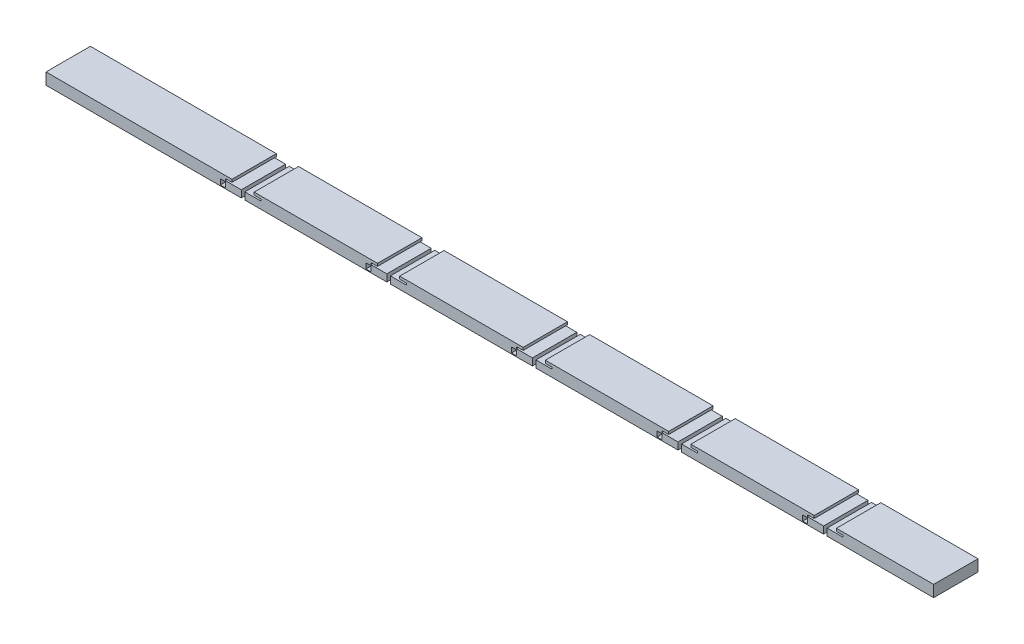
SolidWorks part; units mm, degrees
ref_plane "Front Plane" through (0, 0, 0) normal (0, 0, 1) x (1, 0, 0)
ref_plane "Top Plane" through (0, 0, 0) normal (0, 1, 0) x (1, 0, 0)
ref_plane "Right Plane" through (0, 0, 0) normal (1, 0, 0) x (0, 0, -1)
sketch "Sketch1" plane through (0, 0, 0) normal (0, 1, 0) x (1, 0, 0)
  line L1 (-21.3043, -8.2174) -> (178.6957, -8.2174)
  line L2 (-21.3043, -8.2174) -> (-21.3043, 1.7826)
  line L3 (-21.3043, 1.7826) -> (178.6957, 1.7826)
  line L4 (178.6957, -8.2174) -> (178.6957, 1.7826)
  dimension "D1" = 10
  dimension "D2" = 200
extrude "Boss-Extrude1" add sketch "Sketch1" along normal blind 2.6 contours L1 L4 L3 L2
sketch "Sketch3" plane through (0, 0, 0) normal (0, -1, 0) x (1, 0, 0)
  line L5 (-21.3043, 8.2174) -> (178.6957, 8.2174) construction
  line L6 (22.6957, 8.2174) -> (23.4957, 8.2174)
  line L7 (22.6957, 8.2174) -> (22.6957, -1.7826)
  line L8 (22.6957, -1.7826) -> (23.4957, -1.7826)
  line L9 (23.4957, 8.2174) -> (23.4957, -1.7826)
  line L10 (-21.3043, -1.7826) -> (178.6957, -1.7826) construction
  line L11 (-21.3043, 8.2174) -> (-21.3043, -1.7826) construction
  line L13 (55.4957, 8.2174) -> (56.2957, 8.2174)
  line L14 (55.4957, 8.2174) -> (55.4957, -1.7826)
  line L15 (55.4957, -1.7826) -> (56.2957, -1.7826)
  line L16 (56.2957, 8.2174) -> (56.2957, -1.7826)
  line L17 (88.2957, 8.2174) -> (89.0957, 8.2174)
  line L18 (88.2957, 8.2174) -> (88.2957, -1.7826)
  line L19 (88.2957, -1.7826) -> (89.0957, -1.7826)
  line L20 (89.0957, 8.2174) -> (89.0957, -1.7826)
  line L21 (121.0957, 8.2174) -> (121.8957, 8.2174)
  line L22 (121.0957, 8.2174) -> (121.0957, -1.7826)
  line L23 (121.0957, -1.7826) -> (121.8957, -1.7826)
  line L24 (121.8957, 8.2174) -> (121.8957, -1.7826)
  line L25 (153.8957, 8.2174) -> (154.6957, 8.2174)
  line L26 (153.8957, 8.2174) -> (153.8957, -1.7826)
  line L27 (153.8957, -1.7826) -> (154.6957, -1.7826)
  line L28 (154.6957, 8.2174) -> (154.6957, -1.7826)
  dimension "D1" = 0.8
  dimension "D2" = 44
  dimension "D3" = 0.8
  dimension "D4" = 32
  dimension "D5" = 0.8
  dimension "D6" = 32
  dimension "D7" = 0.8
  dimension "D8" = 0.8
  dimension "D9" = 32
  dimension "D10" = 32
extrude "Cut-Extrude1" cut sketch "Sketch3" against normal blind 2
sketch "Sketch4" plane through (0, 2.6, 0) normal (0, 1, 0) x (1, 0, 0)
  line L0 (-21.3043, 1.7826) -> (178.6957, 1.7826) construction
  line L1 (151.7957, 1.7826) -> (156.7957, 1.7826)
  line L2 (151.7957, 1.7826) -> (151.7957, -8.2174)
  line L3 (151.7957, -8.2174) -> (156.7957, -8.2174)
  line L4 (156.7957, 1.7826) -> (156.7957, -8.2174)
  line L5 (-21.3043, -8.2174) -> (178.6957, -8.2174) construction
  line L7 (123.9957, 1.7826) -> (118.9957, 1.7826)
  line L8 (123.9957, 1.7826) -> (123.9957, -8.2174)
  line L9 (123.9957, -8.2174) -> (118.9957, -8.2174)
  line L10 (118.9957, 1.7826) -> (118.9957, -8.2174)
  line L11 (91.1957, 1.7826) -> (86.1957, 1.7826)
  line L12 (91.1957, 1.7826) -> (91.1957, -8.2174)
  line L13 (91.1957, -8.2174) -> (86.1957, -8.2174)
  line L14 (86.1957, 1.7826) -> (86.1957, -8.2174)
  line L16 (53.3957, 1.7826) -> (58.3957, 1.7826)
  line L17 (53.3957, 1.7826) -> (53.3957, -8.2174)
  line L18 (53.3957, -8.2174) -> (58.3957, -8.2174)
  line L19 (58.3957, 1.7826) -> (58.3957, -8.2174)
  line L20 (20.5957, 1.7826) -> (25.5957, 1.7826)
  line L21 (20.5957, 1.7826) -> (20.5957, -8.2174)
  line L22 (20.5957, -8.2174) -> (25.5957, -8.2174)
  line L23 (25.5957, 1.7826) -> (25.5957, -8.2174)
  line L26 (-21.3043, -8.2174) -> (-21.3043, 1.7826) construction
  dimension "D1" = 5
  dimension "D2" = 27.8
  dimension "D3" = 41.9
  dimension "D4" = 5
  dimension "D5" = 5
  dimension "D6" = 27.8
  dimension "D7" = 5
  dimension "D8" = 5
  dimension "D9" = 27.8
  dimension "D10" = 27.8
extrude "Cut-Extrude2" cut sketch "Sketch4" against normal blind 0.6
sketch "Sketch5" plane through (0, 2, 0) normal (0, 1, 0) x (1, 0, 0)
  line L0 (118.9957, -8.2174) -> (121.0957, -8.2174) construction
  line L1 (86.1957, 1.7826) -> (91.1957, 1.7826)
  line L2 (86.1957, 1.7826) -> (86.1957, -8.2174)
  line L3 (86.1957, -8.2174) -> (91.1957, -8.2174)
  line L4 (91.1957, 1.7826) -> (91.1957, -8.2174)
  line L5 (118.9957, 1.7826) -> (123.9957, 1.7826)
  line L6 (118.9957, 1.7826) -> (118.9957, -8.2174)
  line L7 (118.9957, -8.2174) -> (123.9957, -8.2174)
  line L8 (123.9957, 1.7826) -> (123.9957, -8.2174)
  line L9 (123.9957, -8.2174) -> (123.9957, 1.7826) construction
  line L11 (151.7957, 1.7826) -> (156.7957, 1.7826)
  line L12 (151.7957, 1.7826) -> (151.7957, -8.2174)
  line L13 (151.7957, -8.2174) -> (156.7957, -8.2174)
  line L14 (156.7957, 1.7826) -> (156.7957, -8.2174)
  line L15 (53.3957, 1.7826) -> (58.3957, 1.7826)
  line L16 (53.3957, 1.7826) -> (53.3957, -8.2174)
  line L17 (53.3957, -8.2174) -> (58.3957, -8.2174)
  line L18 (58.3957, 1.7826) -> (58.3957, -8.2174)
  line L19 (20.5957, 1.7826) -> (25.5957, 1.7826)
  line L20 (20.5957, 1.7826) -> (20.5957, -8.2174)
  line L21 (20.5957, -8.2174) -> (25.5957, -8.2174)
  line L22 (25.5957, 1.7826) -> (25.5957, -8.2174)
extrude "Boss-Extrude2" add sketch "Sketch5" along normal blind 0.6 separate body
ref_plane "Plane1" through (0, 2, 0) normal (0, 1, 0) x (1, 0, 0)
sketch "Sketch6" plane through (0, 2, 0) normal (0, 1, 0) x (1, 0, 0)
  line L0 (156.7957, 1.7826) -> (151.7957, 1.7826) construction
  line L2 (154.6957, 1.7826) -> (154.6957, -8.2174)
  line L5 (25.5957, -8.2174) -> (53.3957, -8.2174) construction
  line L6 (23.4957, 1.7826) -> (27.0957, 1.7826)
  line L8 (153.8957, 1.7826) -> (153.8957, -8.2174)
  line L11 (156.7957, -8.2174) -> (156.7957, 1.7826) construction
  line L13 (121.8957, 1.7826) -> (121.8957, -8.2174)
  line L17 (121.0957, 1.7826) -> (121.0957, -8.2174)
  line L20 (118.9957, 1.7826) -> (118.9957, -8.2174) construction
  line L25 (89.0957, 1.7826) -> (89.0957, -8.2174)
  line L29 (88.2957, 1.7826) -> (88.2957, -8.2174)
  line L33 (56.2957, 1.7826) -> (56.2957, -8.2174)
  line L37 (55.4957, 1.7826) -> (55.4957, -8.2174)
  line L48 (53.3957, 1.7826) -> (53.3957, -8.2174) construction
  line L50 (23.4957, 1.7826) -> (23.4957, -8.2174)
  line L51 (23.4957, -8.2174) -> (27.0957, -8.2174)
  line L54 (86.1957, 1.7826) -> (86.1957, -8.2174) construction
  line L121 (27.0957, 1.7826) -> (27.0957, -8.2174)
  line L122 (25.5957, 1.7826) -> (20.5957, 1.7826) construction
  line L123 (22.6957, 1.7826) -> (19.0957, 1.7826)
  line L124 (22.6957, 1.7826) -> (22.6957, -8.2174)
  line L125 (22.6957, -8.2174) -> (19.0957, -8.2174)
  line L126 (19.0957, 1.7826) -> (19.0957, -8.2174)
  line L127 (-21.3043, -8.2174) -> (20.5957, -8.2174) construction
  line L128 (20.5957, 1.7826) -> (20.5957, -8.2174) construction
  line L130 (58.3957, 1.7826) -> (86.1957, 1.7826) construction
  line L140 (56.2957, 1.7826) -> (59.8957, 1.7826)
  line L141 (59.8957, 1.7826) -> (59.8957, -8.2174)
  line L142 (58.3957, -8.2174) -> (86.1957, -8.2174) construction
  line L143 (59.8957, -8.2174) -> (56.2957, -8.2174)
  line L144 (55.4957, 1.7826) -> (51.8957, 1.7826)
  line L145 (25.5957, 1.7826) -> (53.3957, 1.7826) construction
  line L146 (51.8957, 1.7826) -> (51.8957, -8.2174)
  line L147 (51.8957, -8.2174) -> (55.4957, -8.2174)
  line L148 (88.2957, 1.7826) -> (84.6957, 1.7826)
  line L149 (89.0957, 1.7826) -> (92.6957, 1.7826)
  line L150 (91.1957, 1.7826) -> (118.9957, 1.7826) construction
  line L151 (84.6957, 1.7826) -> (84.6957, -8.2174)
  line L152 (84.6957, -8.2174) -> (88.2957, -8.2174)
  line L153 (92.6957, 1.7826) -> (92.6957, -8.2174)
  line L154 (91.1957, -8.2174) -> (118.9957, -8.2174) construction
  line L155 (92.6957, -8.2174) -> (89.0957, -8.2174)
  line L156 (121.0957, -8.2174) -> (117.4957, -8.2174)
  line L157 (121.8957, -8.2174) -> (125.4957, -8.2174)
  line L158 (123.9957, -8.2174) -> (151.7957, -8.2174) construction
  line L159 (117.4957, -8.2174) -> (117.4957, 1.7826)
  line L160 (117.4957, 1.7826) -> (121.0957, 1.7826)
  line L161 (125.4957, -8.2174) -> (125.4957, 1.7826)
  line L162 (123.9957, 1.7826) -> (151.7957, 1.7826) construction
  line L163 (125.4957, 1.7826) -> (121.8957, 1.7826)
  line L164 (154.6957, -8.2174) -> (158.2957, -8.2174)
  line L165 (156.7957, -8.2174) -> (178.6957, -8.2174) construction
  line L166 (153.8957, -8.2174) -> (150.2957, -8.2174)
  line L167 (150.2957, -8.2174) -> (150.2957, 1.7826)
  line L168 (150.2957, 1.7826) -> (153.8957, 1.7826)
  line L169 (158.2957, -8.2174) -> (158.2957, 1.7826)
  line L170 (156.7957, 1.7826) -> (178.6957, 1.7826) construction
  line L171 (158.2957, 1.7826) -> (154.6957, 1.7826)
  dimension "D1" = 0.8
  dimension "D2" = 2.1
  dimension "D3" = 3.6
  dimension "D5" = 0.8
  dimension "D6" = 3.6
  dimension "D8" = 2.1
  dimension "D9" = 0.8
  dimension "D12" = 0.8
  dimension "D13" = 3.6
  dimension "D15" = 3.6
  dimension "D16" = 0.8
  dimension "D17" = 3.6
  dimension "D18" = 2.1
  dimension "D19" = 2.1
  dimension "D21" = 2.1
extrude "Cut-Extrude3" cut sketch "Sketch6" against normal blind 0.4
sketch "Sketch11" plane through (0, 0, 8.2174) normal (0, 0, 1) x (1, 0, 0)
  line L0 (86.1957, 2.6) -> (86.1957, 2) construction
  line L5 (118.9957, 2) -> (118.9957, 2.6) construction
  line L6 (151.7957, 2.6) -> (151.7957, 2) construction
  line L39 (53.3957, 2.6) -> (53.3957, 2) construction
  line L44 (20.5957, 2.6) -> (20.5957, 2) construction
  line L49 (19.0957, 1.4) -> (17.9957, 1.4)
  line L54 (19.0957, 1.4) -> (19.0957, 0.2)
  line L79 (19.0957, 0.2) -> (17.9957, 0.2)
  line L84 (17.9957, 1.4) -> (17.9957, 0.2)
  line L85 (-21.3043, 2.6) -> (20.5957, 2.6) construction
  line L94 (25.5957, 2.6) -> (53.3957, 2.6) construction
  line L95 (58.3957, 2.6) -> (86.1957, 2.6) construction
  line L96 (91.1957, 2.6) -> (118.9957, 2.6) construction
  line L97 (123.9957, 2.6) -> (151.7957, 2.6) construction
  line L98 (50.7957, 1.4) -> (51.8957, 1.4)
  line L99 (50.7957, 1.4) -> (50.7957, 0.2)
  line L100 (50.7957, 0.2) -> (51.8957, 0.2)
  line L101 (51.8957, 1.4) -> (51.8957, 0.2)
  line L102 (83.5957, 1.4) -> (84.6957, 1.4)
  line L103 (83.5957, 1.4) -> (83.5957, 0.2)
  line L104 (83.5957, 0.2) -> (84.6957, 0.2)
  line L105 (84.6957, 1.4) -> (84.6957, 0.2)
  line L106 (116.3957, 1.4) -> (117.4957, 1.4)
  line L107 (116.3957, 1.4) -> (116.3957, 0.2)
  line L108 (116.3957, 0.2) -> (117.4957, 0.2)
  line L109 (117.4957, 1.4) -> (117.4957, 0.2)
  line L110 (149.1957, 1.4) -> (150.2957, 1.4)
  line L111 (149.1957, 1.4) -> (149.1957, 0.2)
  line L112 (149.1957, 0.2) -> (150.2957, 0.2)
  line L113 (150.2957, 1.4) -> (150.2957, 0.2)
  point P28 (117.4957, 0.8)
  point P33 (151.7957, 2.3)
  dimension "D2" = 1.1
  dimension "D3" = 1.5
  dimension "D4" = 1.1
  dimension "D5" = 1.5
  dimension "D6" = 1.1
  dimension "D7" = 1.5
  dimension "D8" = 1.1
  dimension "D9" = 1.1
  dimension "D10" = 1.5
  dimension "D11" = 1.5
  dimension "D12" = 1.2
  dimension "D13" = 1.2
  dimension "D14" = 1.2
  dimension "D15" = 1.2
  dimension "D16" = 1.2
  dimension "D17" = 1.2
  dimension "D18" = 1.2
  dimension "D19" = 1.2
  dimension "D20" = 1.2
  dimension "D21" = 1.2
extrude "Cut-Extrude4" cut sketch "Sketch11" against normal blind 5
sketch "Sketch12" plane through (0, 2.6, 0) normal (0, 1, 0) x (1, 0, 0)
  line L0 (25.5957, -8.2174) -> (25.5957, 1.7826) construction
  line L1 (20.5957, 1.7826) -> (25.5957, 1.7826)
  line L2 (20.5957, 1.7826) -> (20.5957, -8.2174)
  line L3 (20.5957, -8.2174) -> (25.5957, -8.2174)
  line L4 (25.5957, 1.7826) -> (25.5957, -8.2174)
  line L6 (53.3957, 1.7826) -> (58.3957, 1.7826)
  line L7 (53.3957, 1.7826) -> (53.3957, -8.2174)
  line L8 (53.3957, -8.2174) -> (58.3957, -8.2174)
  line L9 (58.3957, 1.7826) -> (58.3957, -8.2174)
  line L10 (86.1957, 1.7826) -> (91.1957, 1.7826)
  line L11 (86.1957, 1.7826) -> (86.1957, -8.2174)
  line L12 (86.1957, -8.2174) -> (91.1957, -8.2174)
  line L13 (91.1957, 1.7826) -> (91.1957, -8.2174)
  line L14 (118.9957, 1.7826) -> (123.9957, 1.7826)
  line L15 (118.9957, 1.7826) -> (118.9957, -8.2174)
  line L16 (118.9957, -8.2174) -> (123.9957, -8.2174)
  line L17 (123.9957, 1.7826) -> (123.9957, -8.2174)
  line L18 (151.7957, 1.7826) -> (156.7957, 1.7826)
  line L19 (151.7957, 1.7826) -> (151.7957, -8.2174)
  line L20 (151.7957, -8.2174) -> (156.7957, -8.2174)
  line L21 (156.7957, 1.7826) -> (156.7957, -8.2174)
extrude "Cut-Extrude6" cut sketch "Sketch12" against normal blind 0.6
